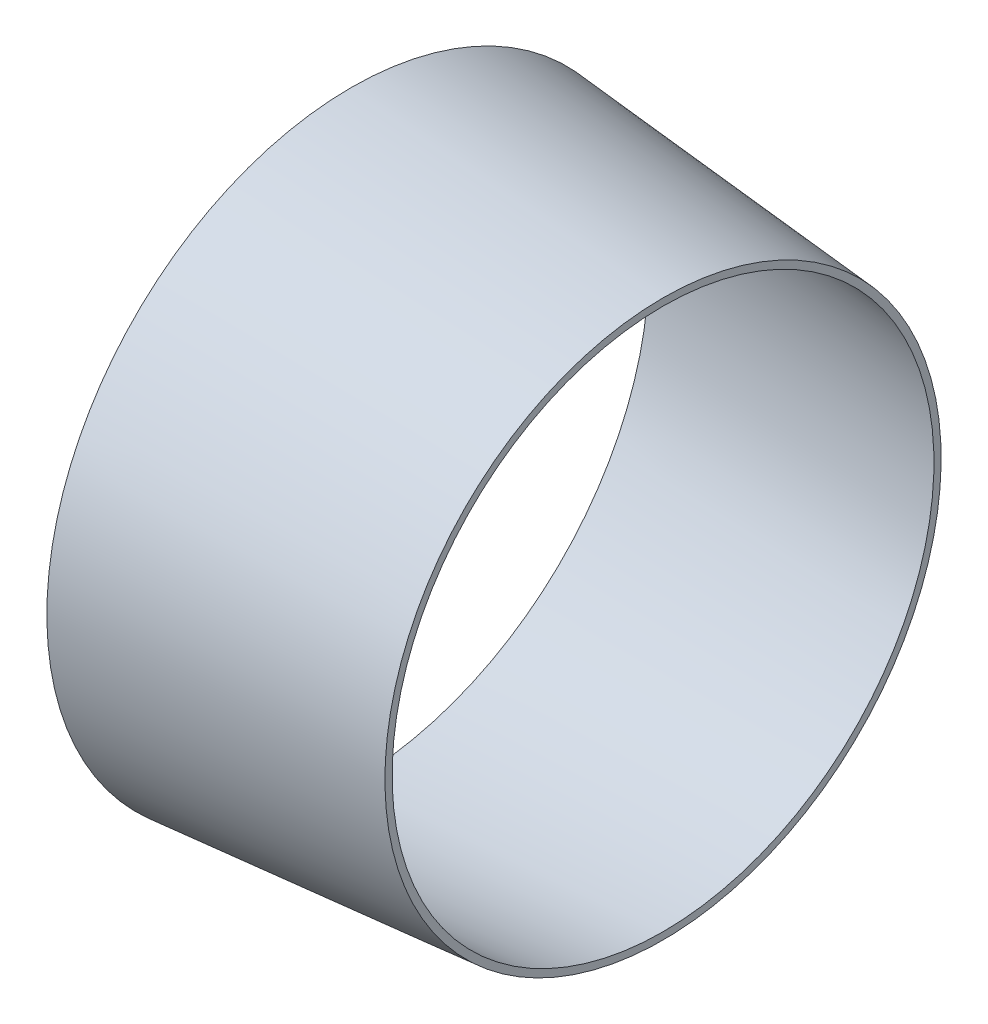
SolidWorks part; units mm, degrees
ref_plane "Front Plane" through (0, 0, 0) normal (0, 0, 1) x (1, 0, 0)
ref_plane "Top Plane" through (0, 0, 0) normal (0, 1, 0) x (1, 0, 0)
ref_plane "Right Plane" through (0, 0, 0) normal (1, 0, 0) x (0, 0, -1)
sketch "Sketch1" plane through (0, 0, 0) normal (0, 0, 1) x (1, 0, 0)
  line L0 (0, 0) -> (5000, 0) construction
  line L1 (3700, 620) -> (3700, 635)
  line L2 (3700, 635) -> (4350, 580)
  line L3 (4350, 580) -> (4350, 565)
  line L4 (4350, 565) -> (3700, 620)
revolve "Revolve1" add sketch "Sketch1" angle 360 about L0
